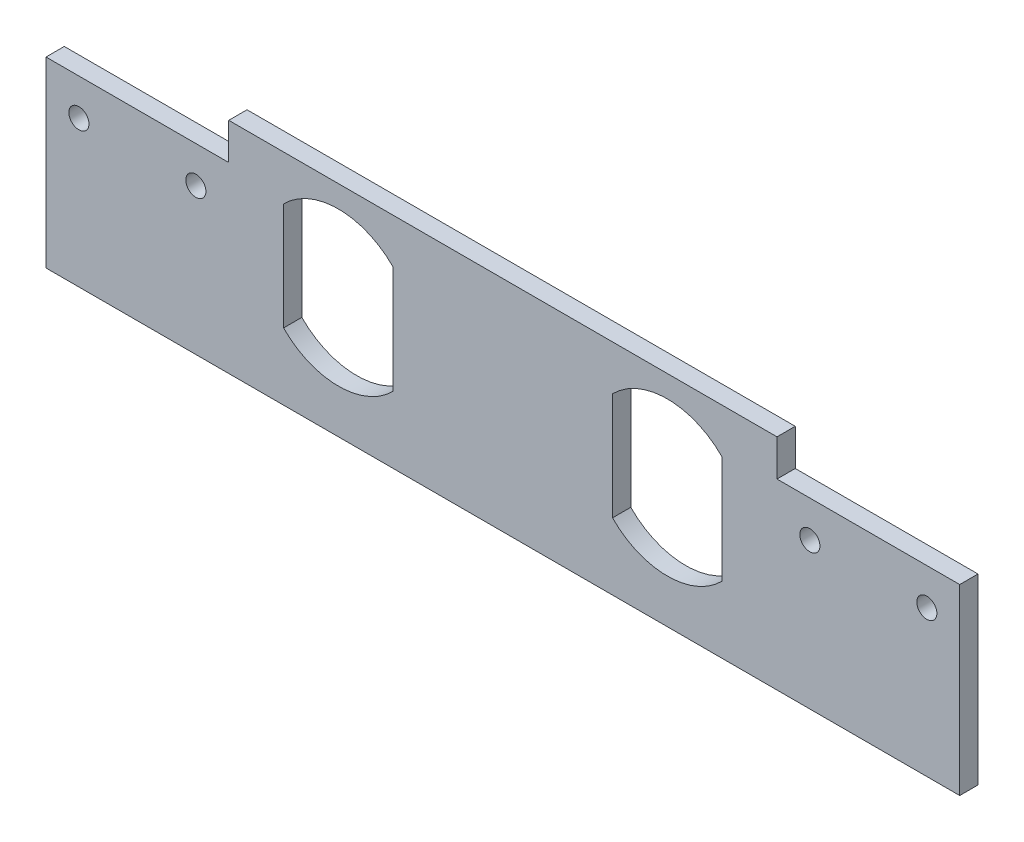
SolidWorks part; units mm, degrees
ref_plane "정면" through (0, 0, 0) normal (0, 0, 1) x (1, 0, 0)
ref_plane "윗면" through (0, 0, 0) normal (0, 1, 0) x (1, 0, 0)
ref_plane "우측면" through (0, 0, 0) normal (1, 0, 0) x (0, 0, -1)
sketch "스케치1" plane through (0, 0, 0) normal (0, 0, 1) x (1, 0, 0)
  line L1 (-145, 25) -> (145, 25)
  line L2 (-145, 25) -> (-145, -25)
  line L3 (-145, -25) -> (145, -25)
  line L4 (145, 25) -> (145, -25)
  line L5 (-145, 25) -> (145, -25) construction
  line L6 (-145, -25) -> (145, 25) construction
  point P0 (0, 0)
  dimension "D1" = 290
  dimension "D2" = 50
extrude "보스-돌출1" add sketch "스케치1" along normal blind 5
sketch "스케치3" plane through (0, 0, 5) normal (0, 0, 1) x (1, 0, 0)
  line L0 (-145, -25) -> (145, -25) construction
  line L1 (-145, 25) -> (-125, 25)
  line L2 (-145, 25) -> (-145, -25)
  line L3 (-145, -25) -> (-125, -25)
  line L4 (-125, 25) -> (-125, -25)
  dimension "D1" = 20
extrude "컷-돌출1" cut sketch "스케치3" against normal blind 10
mirror "대칭 복사1" about plane through (0, 0, 0) normal (1, 0, 0) of "컷-돌출1"
sketch "스케치4" plane through (0, 25, 0) normal (0, 1, 0) x (1, 0, 0)
  line L0 (125, 0) -> (-125, 0) construction
  line L1 (75, 0) -> (-75, 0)
  line L2 (75, 0) -> (75, -5)
  line L3 (75, -5) -> (-75, -5)
  line L4 (-75, 0) -> (-75, -5)
  line L5 (125, -5) -> (-125, -5) construction
  line L6 (-125, 0) -> (-125, -5) construction
  line L7 (125, 0) -> (125, -5) construction
  dimension "D1" = 50
  dimension "D2" = 50
extrude "보스-돌출2" add sketch "스케치4" along normal blind 10
sketch "스케치5" plane through (0, 0, 5) normal (0, 0, 1) x (1, 0, 0)
  line L0 (-75, 25) -> (-125, 25) construction
  line L1 (-125, -25) -> (-125, 25) construction
  line L2 (0, -2.75) -> (0, 2.75) construction
  circle A0 centre (-84, 15) radius 2.75
  circle A1 centre (-116, 15) radius 2.75
  circle A2 centre (116, 15) radius 2.75
  circle A3 centre (84, 15) radius 2.75
  dimension "D3" = 5.5
  dimension "D4" = 5.5
  dimension "D5" = 9
  dimension "D1" = 10
  dimension "D2" = 10
  dimension "D6" = 41
extrude "컷-돌출4" cut sketch "스케치5" against normal through all
sketch "스케치6" plane through (0, 0, 5) normal (0, 0, 1) x (1, 0, 0)
  line L0 (59.999, 22.6969) -> (59.999, -6.6969)
  line L1 (29.999, 22.6969) -> (29.999, -6.6969)
  line L2 (9.7684, 8) -> (97.0125, 8) construction
  line L3 (44.999, 42.5507) -> (44.999, -41.1439) construction
  line L5 (44.999, 24.24) -> (44.999, -8.25) construction
  line L6 (100.2396, 8) -> (-7.0265, 8) construction
  line L7 (-125, -25) -> (125, -25) construction
  arc A0 (29.999, 22.6969) -> (59.999, 22.6969) centre (44.999, 8) cw
  arc A1 (29.999, -6.6969) -> (59.999, -6.6969) centre (44.999, 8) ccw
  dimension "D2" = 21
  dimension "D3" = 21
  dimension "D4" = 30
  dimension "D1" = 15
  dimension "D9" = 33
extrude "컷-돌출5" cut sketch "스케치6" against normal blind 10
ref_plane "평면1" through (0, 0, 0) normal (-1, 0, 0) x (0, 0, 1)
mirror "대칭 복사2" about plane through (0, 0, 0) normal (-1, 0, 0) of "컷-돌출5"
